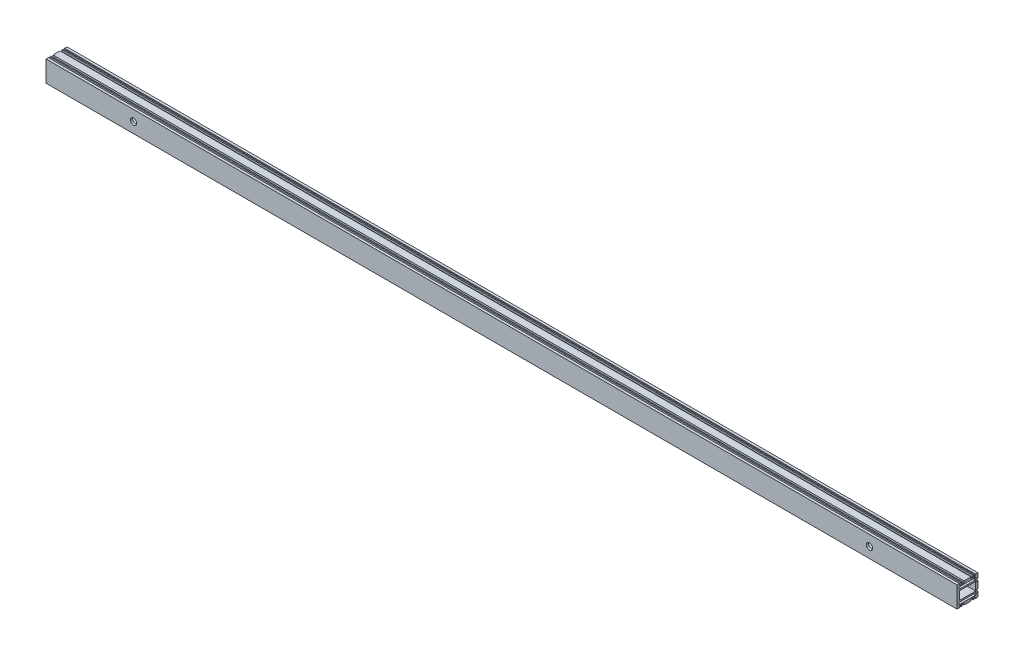
SolidWorks part; units mm, degrees
ref_plane "前视基准面" through (0, 0, 0) normal (0, 0, 1) x (1, 0, 0)
ref_plane "上视基准面" through (0, 0, 0) normal (0, 1, 0) x (1, 0, 0)
ref_plane "右视基准面" through (0, 0, 0) normal (1, 0, 0) x (0, 0, -1)
sketch "草图1" plane through (0, 0, 0) normal (1, 0, 0) x (0, 0, -1)
  line L0 (-15, 15) -> (15, -15) construction
  line L1 (-15, 15) -> (-11.5, 15)
  line L2 (-15, 15) -> (-15, -15)
  line L3 (-15, -15) -> (-11.5, -15)
  line L4 (15, 15) -> (15, 8)
  line L5 (15, 15) -> (-15, -15) construction
  line L6 (-11.5, 15) -> (-11.5, 13.5)
  line L7 (-11.5, 13.5) -> (-11, 13.5)
  line L8 (-11, 13.5) -> (-11, 12)
  line L9 (-11, 12) -> (-9.5, 12)
  line L10 (-9.5, 12) -> (-9.5, 15)
  line L11 (-9.5, 15) -> (-8, 15)
  line L12 (-8, 15) -> (-8, 12.5)
  line L13 (-8, 12.5) -> (-5, 12.5)
  line L14 (-5, 12.5) -> (-5, 15)
  line L15 (-5, 15) -> (5, 15)
  line L16 (0, 21.5201) -> (0, -18.309) construction
  line L17 (0, 55) -> (0, -55) construction
  line L18 (5, 12.5) -> (5, 15)
  line L19 (8, 12.5) -> (5, 12.5)
  line L20 (8, 15) -> (8, 12.5)
  line L21 (9.5, 15) -> (8, 15)
  line L22 (9.5, 12) -> (9.5, 15)
  line L23 (11, 12) -> (9.5, 12)
  line L24 (11, 13.5) -> (11, 12)
  line L25 (11.5, 13.5) -> (11, 13.5)
  line L26 (11.5, 15) -> (11.5, 13.5)
  line L27 (8, 15) -> (9.5, 15)
  line L28 (11.5, 15) -> (15, 15)
  line L29 (-19.8303, 0) -> (22.13, 0) construction
  line L30 (55, 0) -> (-55, 0) construction
  line L31 (8, -15) -> (9.5, -15)
  line L32 (11.5, -15) -> (11.5, -13.5)
  line L33 (11.5, -13.5) -> (11, -13.5)
  line L34 (11, -13.5) -> (11, -12)
  line L35 (11, -12) -> (9.5, -12)
  line L36 (9.5, -12) -> (9.5, -15)
  line L37 (9.5, -15) -> (8, -15)
  line L38 (8, -15) -> (8, -12.5)
  line L39 (8, -12.5) -> (5, -12.5)
  line L40 (5, -12.5) -> (5, -15)
  line L41 (-5, -15) -> (5, -15)
  line L42 (-5, -12.5) -> (-5, -15)
  line L43 (-8, -12.5) -> (-5, -12.5)
  line L44 (-8, -15) -> (-8, -12.5)
  line L45 (-9.5, -15) -> (-8, -15)
  line L46 (-9.5, -12) -> (-9.5, -15)
  line L47 (-11, -12) -> (-9.5, -12)
  line L48 (-11, -13.5) -> (-11, -12)
  line L49 (-11.5, -13.5) -> (-11, -13.5)
  line L50 (-11.5, -15) -> (-11.5, -13.5)
  line L51 (-9.5, -15) -> (-8, -15)
  line L52 (-5, -15) -> (5, -15)
  line L53 (8, -15) -> (9.5, -15)
  line L54 (11.5, -15) -> (15, -15)
  line L55 (15, 8) -> (12.5, 8)
  line L56 (12.5, 8) -> (12.5, 5)
  line L57 (12.5, 5) -> (15, 5)
  line L58 (12.5, -5) -> (15, -5)
  line L59 (12.5, -8) -> (12.5, -5)
  line L60 (15, -8) -> (12.5, -8)
  line L61 (15, 5) -> (15, -5)
  line L62 (15, -8) -> (15, -15)
  line L63 (12, -10.5) -> (12, -8.5)
  line L64 (-11.5, 11) -> (11.5, 11)
  line L65 (-12, 10.5) -> (-12, 8.5)
  line L66 (-11.5, 8) -> (11.5, 8)
  line L67 (12, 10.5) -> (12, 8.5)
  line L68 (-11.5, -8) -> (11.5, -8)
  line L69 (-12, -10.5) -> (-12, -8.5)
  line L70 (-11.5, -11) -> (11.5, -11)
  line L72 (-11.75, 6) -> (11.75, 6)
  line L73 (-11.75, 6) -> (-11.75, -6)
  line L74 (-11.75, -6) -> (11.75, -6)
  line L75 (11.75, 6) -> (11.75, -6)
  arc A0 (12, 8.5) -> (11.5, 8) centre (11.5, 8.5) cw
  arc A1 (11.5, 11) -> (12, 10.5) centre (11.5, 10.5) cw
  arc A2 (-11.5, 11) -> (-12, 10.5) centre (-11.5, 10.5) ccw
  arc A3 (-11.5, 8) -> (-12, 8.5) centre (-11.5, 8.5) cw
  arc A8 (-11.5, -8) -> (-12, -8.5) centre (-11.5, -8.5) ccw
  arc A9 (-11.5, -11) -> (-12, -10.5) centre (-11.5, -10.5) cw
  arc A10 (11.5, -11) -> (12, -10.5) centre (11.5, -10.5) ccw
  arc A11 (12, -8.5) -> (11.5, -8) centre (11.5, -8.5) ccw
  point P69 (12, 11)
  point P72 (-12, 11)
  point P77 (-11, -13.5)
  point P80 (11, -13.5)
  point P83 (11, 13.5)
  point P86 (-11, 13.5)
  point P99 (-12, -11)
  point P100 (12, -11)
  dimension "D17" = 0.5
  dimension "D1" = 3.5
  dimension "D2" = 1.5
  dimension "D3" = 0.5
  dimension "D4" = 1.5
  dimension "D5" = 3
  dimension "D6" = 30
  dimension "D7" = 30
  dimension "D8" = 1.5
  dimension "D9" = 2.5
  dimension "D10" = 3
  dimension "D11" = 2.5
  dimension "D12" = 7
  dimension "D13" = 3
  dimension "D14" = 4
  dimension "D15" = 3
  dimension "D16" = 24
  dimension "D19" = 23.5
  dimension "D20" = 12
extrude "凸台-拉伸1" add sketch "草图1" along normal mid plane 1301
hole_wizard "M6 螺纹孔1" positions "草图3" profile "草图2" tap size "M6" standard "GB"
sketch "草图3" plane through (0, -15, 0) normal (0, -1, 0) x (-1, 0, 0)
  point P0 (630.5, 0)
  point P3 (615.5, 0)
  point P6 (-615.5, 0)
  point P9 (-630.5, 0)
sketch "草图2" plane through (-630.5, -15, 0) normal (1, 0, 0) x (0, 0, -1)
  line L0 (0, 0) -> (0, 20.5022)
  line L1 (0, 20.5022) -> (2.5, 19)
  line L2 (2.5, 19) -> (2.5, 0)
  line L5 (2.5, 0) -> (0, 0)
  line L10 (0, 20.5022) -> (-2.5, 19) construction
  line L11 (0, -6.35) -> (0, 107.95) construction
  dimension "螺纹孔钻头直径" = 5
  dimension "螺纹孔钻头深度" = 19
  dimension "导头角度" = 118
cosmetic thread "孔螺蚊线1" parameters "D1"=9, "D2"=6
cosmetic thread "孔螺蚊线2" parameters "D1"=9, "D2"=6
cosmetic thread "孔螺蚊线3" parameters "D1"=9, "D2"=6
cosmetic thread "孔螺蚊线4" parameters "D1"=9, "D2"=6
hole_wizard "M6 螺纹孔2" positions "草图5" profile "草图4" tap size "M6" standard "GB"
sketch "草图5" plane through (0, 0, -15) normal (0, 0, -1) x (-1, 0, 0)
  point P0 (-630.5, 0)
  point P3 (-615.5, 0)
  point P6 (630.5, 0)
  point P9 (615.5, 0)
sketch "草图4" plane through (630.5, 0, -15) normal (1, 0, 0) x (0, 1, 0)
  line L0 (0, 0) -> (0, 20.5022)
  line L1 (0, 20.5022) -> (2.5, 19)
  line L2 (2.5, 19) -> (2.5, 0)
  line L5 (2.5, 0) -> (0, 0)
  line L10 (0, 20.5022) -> (-2.5, 19) construction
  line L11 (0, -6.35) -> (0, 107.95) construction
  dimension "螺纹孔钻头直径" = 5
  dimension "螺纹孔钻头深度" = 19
  dimension "导头角度" = 118
cosmetic thread "孔螺蚊线5" parameters "D1"=3.25, "D2"=6
cosmetic thread "孔螺蚊线6" parameters "D1"=3.25, "D2"=6
cosmetic thread "孔螺蚊线7" parameters "D1"=3.25, "D2"=6
cosmetic thread "孔螺蚊线8" parameters "D1"=3.25, "D2"=6
hole_wizard "M4 螺纹孔1" positions "草图7" profile "草图6" tap size "M4" standard "GB"
sketch "草图7" plane through (0, -15, 0) normal (0, -1, 0) x (-1, 0, 0)
  line L0 (-650.5, 15) -> (650.5, 15) construction
  line L1 (-650.5, 11.5) -> (-650.5, 15) construction
  line L2 (-650.5, 15) -> (650.5, 15) construction
  line L3 (-650.5, 15) -> (650.5, 15) construction
  line L4 (650.5, -5) -> (650.5, 5) construction
  line L5 (650.5, 11.5) -> (650.5, 15) construction
  point P0 (560, 0)
  point P2 (280, 0)
  point P4 (0, 0)
  point P6 (-280, 0)
  point P8 (-560, 0)
  dimension "D1" = 15
  dimension "D2" = 90.5
  dimension "D3" = 370.5
  dimension "D4" = 15
  dimension "D5" = 15
  dimension "D6" = 650.5
  dimension "D7" = 15
  dimension "D8" = 370.5
  dimension "D9" = 15
  dimension "D10" = 90.5
sketch "草图6" plane through (-560, -15, 0) normal (1, 0, 0) x (0, 0, -1)
  line L0 (0, 0) -> (0, 16.4914)
  line L1 (0, 16.4914) -> (1.65, 15.5)
  line L2 (1.65, 15.5) -> (1.65, 0)
  line L5 (1.65, 0) -> (0, 0)
  line L10 (0, 16.4914) -> (-1.65, 15.5) construction
  line L11 (0, -6.35) -> (0, 107.95) construction
  dimension "螺纹孔钻头直径" = 3.3
  dimension "螺纹孔钻头深度" = 15.5
  dimension "导头角度" = 118
cosmetic thread "孔螺蚊线9" parameters "D1"=9, "D2"=4
cosmetic thread "孔螺蚊线10" parameters "D1"=9, "D2"=4
cosmetic thread "孔螺蚊线11" parameters "D1"=9, "D2"=4
cosmetic thread "孔螺蚊线12" parameters "D1"=9, "D2"=4
cosmetic thread "孔螺蚊线13" parameters "D1"=9, "D2"=4
hole_wizard "Ø9.0 (9) 直径孔1" positions "草图9" profile "草图8" hole size "Ø9.0" standard "GB" end condition through all
sketch "草图9" plane through (0, 0, 15) normal (0, 0, 1) x (1, 0, 0)
  line L0 (650.5, -15) -> (-650.5, -15) construction
  line L1 (-650.5, 15) -> (-650.5, -15) construction
  line L2 (650.5, 15) -> (650.5, -15) construction
  point P0 (525.5, 0)
  point P2 (-525.5, 0)
  dimension "D1" = 15
  dimension "D2" = 125
  dimension "D3" = 15
  dimension "D4" = 125
sketch "草图8" plane through (525.5, 0, 15) normal (1, 0, 0) x (0, -1, 0)
  line L0 (0, 0) -> (0, 30)
  line L1 (0, 30) -> (4.5, 30)
  line L2 (4.5, 30) -> (4.5, 0)
  line L5 (4.5, 0) -> (0, 0)
  line L11 (0, -6.35) -> (0, 107.95) construction
  dimension "通孔孔直径" = 9
  dimension "通孔孔深度" = 30
hole_wizard "M4 螺纹孔2" positions "草图11" profile "草图12" tap size "M4" standard "GB"
sketch "草图11" plane through (0, 0, -15) normal (0, 0, -1) x (-1, 0, 0)
  line L0 (-650.5, -15) -> (650.5, -15) construction
  line L1 (650.5, -8) -> (650.5, -15) construction
  line L8 (-650.5, 15) -> (650.5, 15) construction
  line L9 (-650.5, 5) -> (-650.5, -5) construction
  line L10 (-650.5, -8) -> (-650.5, -15) construction
  point P0 (-460, 0)
  point P2 (-230, 0)
  point P4 (0, 0)
  point P7 (230, 0)
  point P9 (460, 0)
  point P37 (-511.5, 0)
  point P39 (-539.5, 0)
  point P44 (539.5, 0)
  point P46 (511.5, 0)
  dimension "D1" = 15
  dimension "D2" = 190.5
  dimension "D3" = 420.5
  dimension "D4" = 15
  dimension "D5" = 15
  dimension "D6" = 420.5
  dimension "D7" = 15
  dimension "D8" = 190.5
  dimension "D9" = 15
  dimension "D10" = 15
  dimension "D11" = 28
  dimension "D12" = 111
  dimension "D13" = 15
  dimension "D14" = 15
  dimension "D15" = 28
  dimension "D16" = 111
sketch "草图12" plane through (460, 0, -15) normal (1, 0, 0) x (0, 1, 0)
  line L0 (0, 0) -> (0, 16.4914)
  line L1 (0, 16.4914) -> (1.65, 15.5)
  line L2 (1.65, 15.5) -> (1.65, 0)
  line L5 (1.65, 0) -> (0, 0)
  line L10 (0, 16.4914) -> (-1.65, 15.5) construction
  line L11 (0, -6.35) -> (0, 107.95) construction
  dimension "螺纹孔钻头直径" = 3.3
  dimension "螺纹孔钻头深度" = 15.5
  dimension "导头角度" = 118
cosmetic thread "孔螺蚊线14" parameters "D1"=3.25, "D2"=4
cosmetic thread "孔螺蚊线15" parameters "D1"=3.25, "D2"=4
cosmetic thread "孔螺蚊线16" parameters "D1"=3.25, "D2"=4
cosmetic thread "孔螺蚊线17" parameters "D1"=3.25, "D2"=4
cosmetic thread "孔螺蚊线18" parameters "D1"=3.25, "D2"=4
cosmetic thread "孔螺蚊线19" parameters "D1"=3.25, "D2"=4
cosmetic thread "孔螺蚊线20" parameters "D1"=3.25, "D2"=4
cosmetic thread "孔螺蚊线21" parameters "D1"=3.25, "D2"=4
cosmetic thread "孔螺蚊线22" parameters "D1"=3.25, "D2"=4
